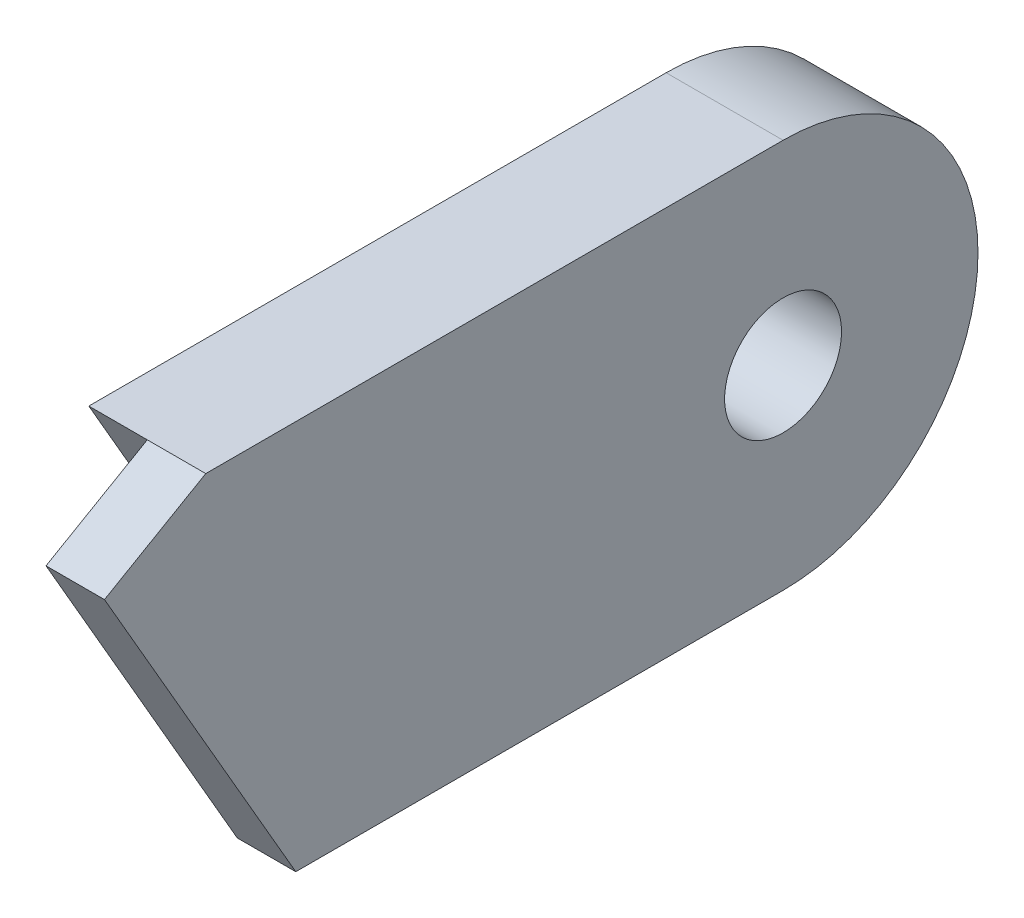
SolidWorks part; units mm, degrees
ref_plane "Front Plane" through (0, 0, 0) normal (0, 0, 1) x (1, 0, 0)
ref_plane "Top Plane" through (0, 0, 0) normal (0, 1, 0) x (1, 0, 0)
ref_plane "Right Plane" through (0, 0, 0) normal (1, 0, 0) x (0, 0, -1)
sketch "Sketch1" plane through (0, 0, 0) normal (1, 0, 0) x (0, 0, -1)
  line L0 (-4.6188, 20) -> (-9.815, 17)
  line L1 (-4.6188, 20) -> (25, 20)
  line L2 (25, 0) -> (0, 0)
  line L3 (-9.815, 17) -> (0, 0)
  arc A0 (25, 20) -> (25, 0) centre (25, 10) cw
  circle A1 centre (25, 10) radius 3
  dimension "D1" = 6
  dimension "D2" = 20
  dimension "D3" = 120
  dimension "D4" = 6
  dimension "D5" = 25
extrude "Boss-Extrude1" add sketch "Sketch1" along normal blind 6
sketch "Sketch2" plane through (0, 0, 0) normal (-1, 0, 0) x (0, 0, 1)
  line L0 (0, 0) -> (-25, 0) construction
  line L1 (9.815, 17) -> (4.6188, 20)
  line L2 (9.815, 17) -> (0, 0)
  line L3 (0, 0) -> (-6.9282, 0)
  line L4 (4.6188, 20) -> (-6.9282, 0)
  line L5 (4.6188, 20) -> (9.815, 17) construction
  dimension "D1" = 6
extrude "Cut-Extrude1" cut sketch "Sketch2" against normal blind 3
